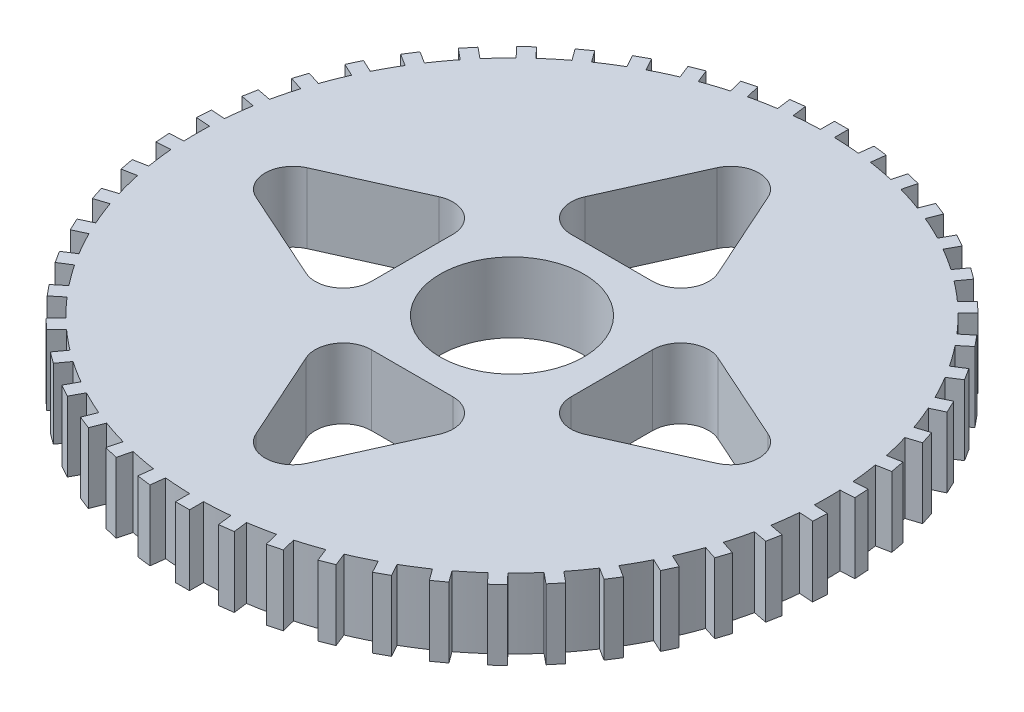
SolidWorks part; units mm, degrees
ref_plane "Front Plane" through (0, 0, 0) normal (0, 0, 1) x (1, 0, 0)
ref_plane "Top Plane" through (0, 0, 0) normal (0, 1, 0) x (1, 0, 0)
ref_plane "Right Plane" through (0, 0, 0) normal (1, 0, 0) x (0, 0, -1)
sketch "Sketch1" plane through (0, 0, 0) normal (0, 1, 0) x (1, 0, 0)
  circle A0 centre (0, 0) radius 22.5
extrude "Boss-Extrude1" add sketch "Sketch1" along normal blind 5
sketch "Sketch2" plane through (0, 5, 0) normal (0, 1, 0) x (1, 0, 0)
  circle A0 centre (0, 0) radius 5.125
extrude "Cut-Extrude1" cut sketch "Sketch2" against normal blind 5
sketch "Sketch3" plane through (0, 5, 0) normal (0, 1, 0) x (1, 0, 0)
  line L0 (7.125, 0) -> (7.125, 6)
  line L1 (7.125, 6) -> (20.5, 0)
  line L2 (0, 7.125) -> (6, 7.125)
  line L3 (0, 7.125) -> (-6, 7.125)
  line L4 (-6, 7.125) -> (0, 20.5)
  line L5 (0, 20.5) -> (6, 7.125)
  line L6 (20.5, 0) -> (7.125, -6)
  line L7 (7.125, 0) -> (7.125, -6)
  line L8 (0, -7.125) -> (6, -7.125)
  line L9 (6, -7.125) -> (0, -20.5)
  line L10 (0, -20.5) -> (-6, -7.125)
  line L11 (0, -7.125) -> (-6, -7.125)
  line L12 (-7.125, 0) -> (-7.125, -6)
  line L13 (-7.125, -6) -> (-20.5, 0)
  line L14 (-20.5, 0) -> (-7.125, 6)
  line L15 (-7.125, 0) -> (-7.125, 6)
  point P22 (0, 0)
  dimension "D1" = 4
extrude "Cut-Extrude2" cut sketch "Sketch3" against normal blind 5
fillet "Fillet1" radius 2 12 edges at (6, 2.5, 7.125) (-6, 2.5, 7.125) (0, 2.5, 20.5) (20.5, 2.5, 0) (7.125, 2.5, 6) (7.125, 2.5, -6) (6, 2.5, -7.125) (-6, 2.5, -7.125) (0, 2.5, -20.5) (-7.125, 2.5, 6) (-20.5, 2.5, 0) (-7.125, 2.5, -6)
sketch "Sketch4" plane through (0, 5, 0) normal (0, 1, 0) x (1, 0, 0)
  line L0 (0, 22.5) -> (0, 23.5)
  line L1 (0, 23.5) -> (0.5, 23.5)
  line L2 (0.5, 23.5) -> (0.5, 22.4944)
  line L3 (0, 23.5) -> (-0.5, 23.5)
  line L4 (-0.5, 23.5) -> (-0.5, 22.4944)
  circle A0 centre (0, 0) radius 22.5 construction
  arc A1 (-0.5, 22.4944) -> (0.5, 22.4944) centre (0, 0) cw
  circle M27 centre (0, 0) radius 22.5
extrude "Boss-Extrude2" add sketch "Sketch4" against normal up to surface (5 mm away) contours L2 L1 L0 M27 | L3 L4 L0 M27 up to face at (11.1984, 0, 0)
pattern_circular "CirPattern1" count 50 over 360 about axis through (0, 0, 0) along (0, 1, 0) of "Boss-Extrude2"
